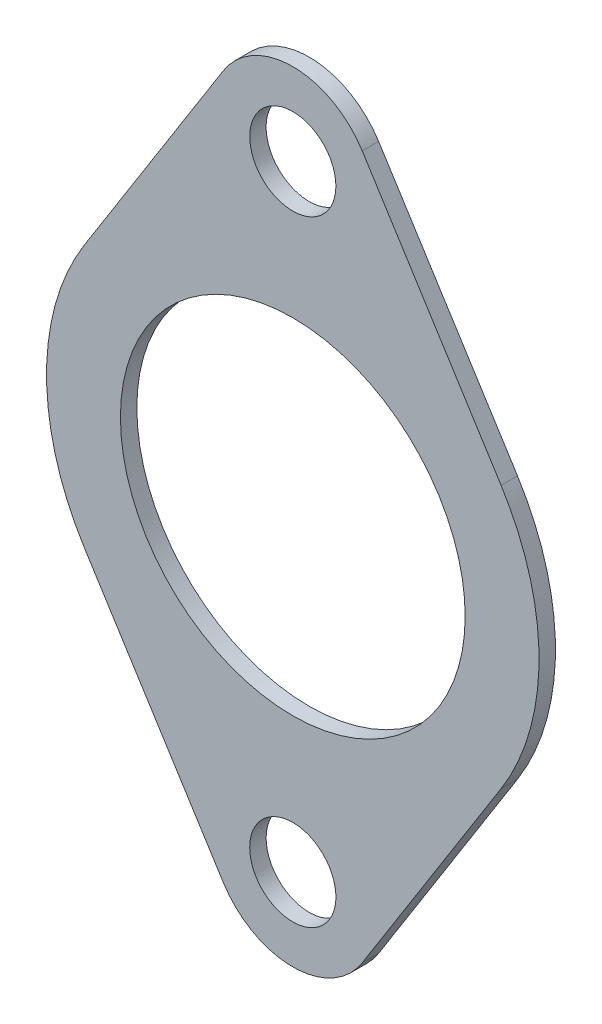
SolidWorks part; units mm, degrees
material "Thornel Mat VMA"
ref_plane "Front Plane" through (0, 0, 0) normal (0, 0, 1) x (1, 0, 0)
ref_plane "Top Plane" through (0, 0, 0) normal (0, 1, 0) x (1, 0, 0)
ref_plane "Right Plane" through (0, 0, 0) normal (1, 0, 0) x (0, 0, -1)
sketch "Sketch3" plane through (0, 0, 0) normal (0, 0, 1) x (1, 0, 0)
  line L0 (0, 56.6799) -> (0, -72.6414) construction
  line L1 (-96.6136, 0) -> (123.8428, 0) construction
  line L2 (8.4591, 42.8333) -> (25.3772, 16)
  line L3 (-8.4591, 42.8333) -> (-25.3772, 16)
  line L4 (-8.4591, -42.8333) -> (-25.3772, -16)
  line L5 (8.4591, -42.8333) -> (25.3772, -16)
  arc A0 (25.3772, -16) -> (25.3772, 16) centre (0, 0) ccw
  arc A1 (8.4591, 42.8333) -> (-8.4591, 42.8333) centre (0, 37.5) ccw
  circle A2 centre (0, 37.5) radius 5.25
  circle A3 centre (0, 0) radius 21
  arc A4 (-25.3772, -16) -> (-25.3772, 16) centre (0, 0) cw
  circle A5 centre (0, -37.5) radius 5.25
  arc A6 (8.4591, -42.8333) -> (-8.4591, -42.8333) centre (0, -37.5) cw
  dimension "D1" = 10
  dimension "D2" = 30
  dimension "D3" = 42
  dimension "D4" = 10.5
  dimension "D5" = 75
extrude "Boss-Extrude1" add sketch "Sketch3" along normal blind 2
